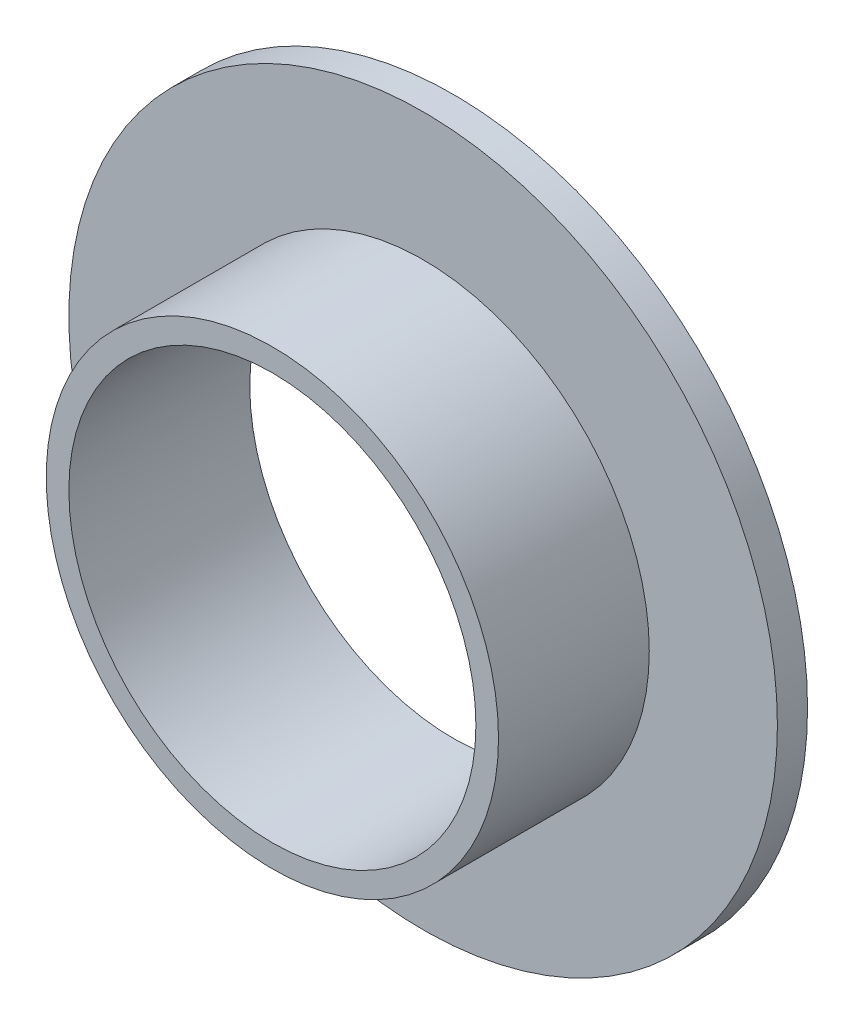
SolidWorks part; units mm, degrees
ref_plane "Front Plane" through (0, 0, 0) normal (0, 0, 1) x (1, 0, 0)
ref_plane "Top Plane" through (0, 0, 0) normal (0, 1, 0) x (1, 0, 0)
ref_plane "Right Plane" through (0, 0, 0) normal (1, 0, 0) x (0, 0, -1)
sketch "Sketch1" plane through (0, 0, 0) normal (0, 0, 1) x (1, 0, 0)
  circle A0 centre (0, 0) radius 23.5
  dimension "D1" = 47
extrude "Boss-Extrude1" add sketch "Sketch1" along normal blind 2
sketch "Sketch2" plane through (0, 0, 2) normal (0, 0, 1) x (1, 0, 0)
  circle A0 centre (0, 0) radius 15
  circle A1 centre (0, 0) radius 13.5
  dimension "D1" = 30
  dimension "D2" = 27
extrude "Boss-Extrude2" add sketch "Sketch2" along normal blind 10
sketch "Sketch4" plane through (0, 0, 0) normal (0, 0, -1) x (-1, 0, 0)
  circle A0 centre (0, 0) radius 13.5
  dimension "D1" = 27
extrude "Cut-Extrude1" cut sketch "Sketch4" against normal blind 10
